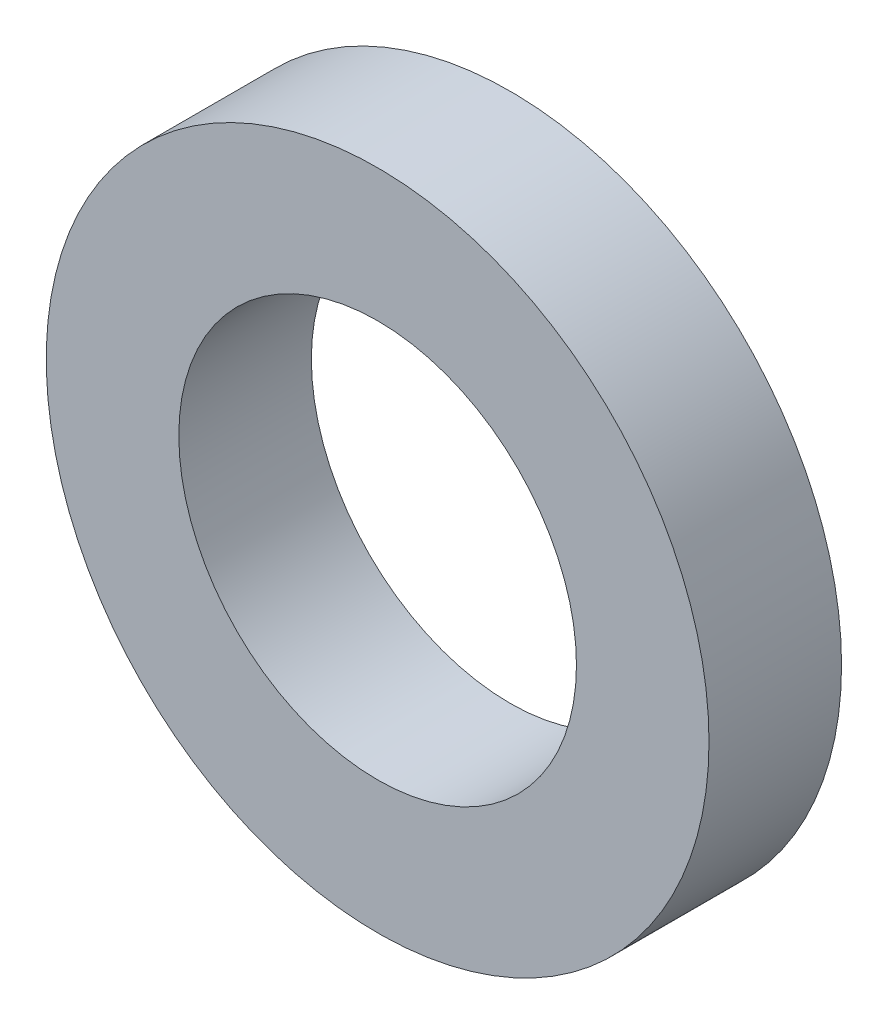
SolidWorks part; units mm, degrees
ref_plane "前视基准面" through (0, 0, 0) normal (0, 0, 1) x (1, 0, 0)
ref_plane "上视基准面" through (0, 0, 0) normal (0, 1, 0) x (1, 0, 0)
ref_plane "右视基准面" through (0, 0, 0) normal (1, 0, 0) x (0, 0, -1)
other "Configuration Table"
sketch "草图1" plane through (0, 0, 0) normal (0, 0, 1) x (1, 0, 0)
  circle A0 centre (0, 0) radius 1.5
  circle A1 centre (0, 0) radius 2.5
  dimension "D1" = 3
  dimension "D2" = 5
extrude "凸台-拉伸1" add sketch "草图1" along normal blind 1
